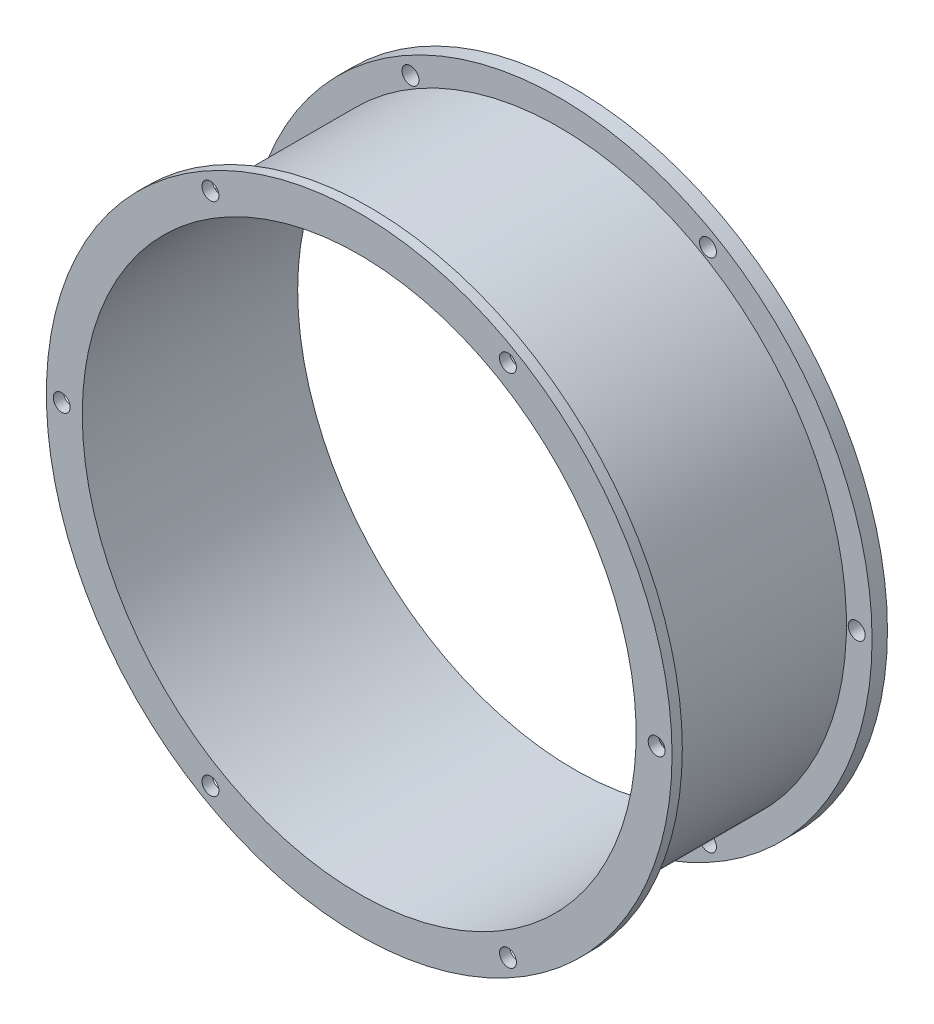
SolidWorks part; units mm, degrees
ref_plane "Спереди" through (0, 0, 0) normal (0, 0, 1) x (1, 0, 0)
ref_plane "Сверху" through (0, 0, 0) normal (0, 1, 0) x (1, 0, 0)
ref_plane "Справа" through (0, 0, 0) normal (1, 0, 0) x (0, 0, -1)
sketch "Эскиз1" plane through (0, 0, 0) normal (0, 0, 1) x (1, 0, 0)
  circle A0 centre (0, 0) radius 56
  circle A1 centre (0, 0) radius 54
extrude "Jacket" add sketch "Эскиз1" along normal blind 42 from offset 27
sketch "Эскиз2" plane through (0, 0, 0) normal (0, 0, 1) x (1, 0, 0)
  circle A0 centre (0, 0) radius 61
  circle A1 centre (0, 0) radius 54
extrude "Rear_flange" add sketch "Эскиз2" along normal blind 3 from offset 27
sketch "Эскиз3" plane through (0, 0, 0) normal (0, 0, 1) x (1, 0, 0)
  circle A0 centre (0, 0) radius 61
  circle A1 centre (0, 0) radius 54
extrude "Front_flange" add sketch "Эскиз3" along normal blind 2 from offset 13
sketch "Эскиз4" plane through (0, 0, 0) normal (0, 0, 1) x (1, 0, 0)
  circle A0 centre (58, 0) radius 1.65
  circle A1 centre (29, 50.2295) radius 1.65
  circle A2 centre (-29, 50.2295) radius 1.65
  circle A3 centre (-58, 0) radius 1.65
  circle A4 centre (-29, -50.2295) radius 1.65
  circle A5 centre (29, -50.2295) radius 1.65
extrude "Through_holes" cut sketch "Эскиз4" against normal mid plane 200
